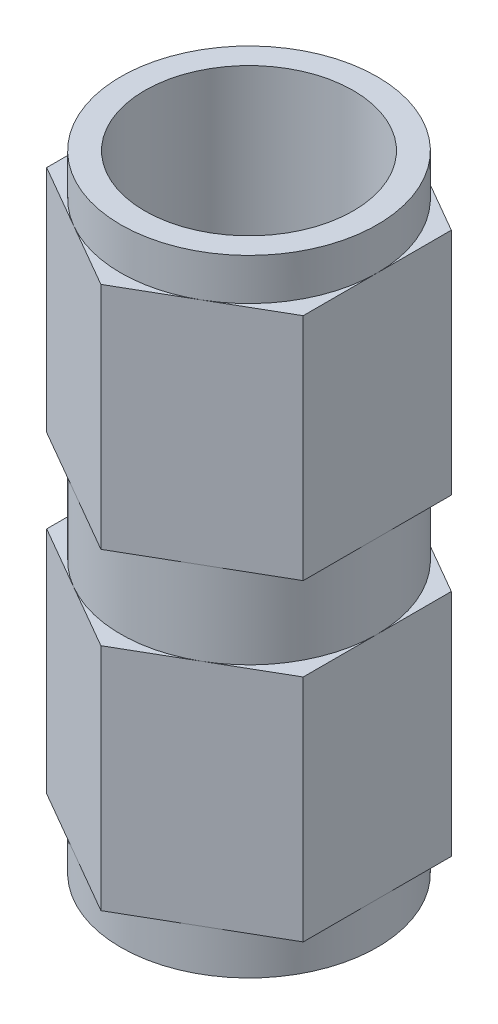
SolidWorks part; units mm, degrees
ref_plane "Front Plane" through (0, 0, 0) normal (0, 0, 1) x (1, 0, 0)
ref_plane "Top Plane" through (0, 0, 0) normal (0, 1, 0) x (1, 0, 0)
ref_plane "Right Plane" through (0, 0, 0) normal (1, 0, 0) x (0, 0, -1)
sketch "Sketch1" plane through (0, 0, 0) normal (0, 1, 0) x (1, 0, 0)
  line L0 (0, 0) -> (0, 9.017)
  line L1 (0, 9.017) -> (-7.809, 4.5085)
  line L2 (-7.809, 4.5085) -> (-7.809, -4.5085)
  line L3 (-7.809, -4.5085) -> (0, -9.017)
  line L4 (0, -9.017) -> (7.809, -4.5085)
  line L5 (7.809, -4.5085) -> (7.809, 4.5085)
  line L6 (7.809, 4.5085) -> (0, 9.017)
  circle A0 centre (0, 0) radius 6.35
  circle A1 centre (0, 0) radius 7.809 construction
  dimension "D1" = 12.7
  dimension "D2" = 18.034
extrude "Boss-Extrude1" add sketch "Sketch1" along normal blind 38.1 contours A0 | L1 L2 L3 L4 L5 L6
sketch "Sketch3" plane through (0, 0, 0) normal (0, -1, 0) x (1, 0, 0)
  circle A1 centre (0, 0) radius 6.35
  circle A2 centre (0, 0) radius 10.9459
  circle A3 centre (0, 0) radius 7.809
  line M3 (0, -9.017) -> (7.809, -4.5085)
  line M4 (7.809, -4.5085) -> (7.809, 4.5085)
  line M5 (7.809, 4.5085) -> (0, 9.017)
  line M6 (0, 9.017) -> (-7.809, 4.5085)
  line M7 (-7.809, 4.5085) -> (-7.809, -4.5085)
  line M8 (-7.809, -4.5085) -> (0, -9.017)
  dimension "D1" = 12.7
extrude "Cut-Extrude1" cut sketch "Sketch3" against normal blind 2.54 contours A3 M7 M8 | A3 M8 M3 | A3 M3 M4 | A3 M4 M5 | A3 M5 M6 | A3 M6 M7 | A2 | A1
sketch "Sketch4" plane through (0, 38.1, 0) normal (0, 1, 0) x (1, 0, 0)
  circle A0 centre (0, 0) radius 6.35
  circle A1 centre (0, 0) radius 7.809
  circle A2 centre (0, 0) radius 13.5241
  line M4 (7.809, 4.5085) -> (0, 9.017)
  line M5 (0, 9.017) -> (-7.809, 4.5085)
  line M6 (-7.809, 4.5085) -> (-7.809, -4.5085)
  line M7 (-7.809, -4.5085) -> (0, -9.017)
  line M8 (0, -9.017) -> (7.809, -4.5085)
  line M9 (7.809, -4.5085) -> (7.809, 4.5085)
extrude "Cut-Extrude2" cut sketch "Sketch4" against normal blind 2.54 contours A1 M6 M7 | A1 M7 M8 | A1 M5 M6 | A1 M4 M5 | A1 M9 M4 | A1 M8 M9
ref_plane "Plane1" through (0, 19.05, 0) normal (0, -1, 0) x (-1, 0, 0)
sketch "Sketch5" plane through (0, 19.05, 0) normal (0, -1, 0) x (-1, 0, 0)
  circle A0 centre (0, 0) radius 6.35
  circle A1 centre (0, 0) radius 7.809
  circle A2 centre (0, 0) radius 11.3573
extrude "Cut-Extrude3" cut sketch "Sketch5" against normal blind 2.54 and the other way blind 2.54 contours A2 A1
